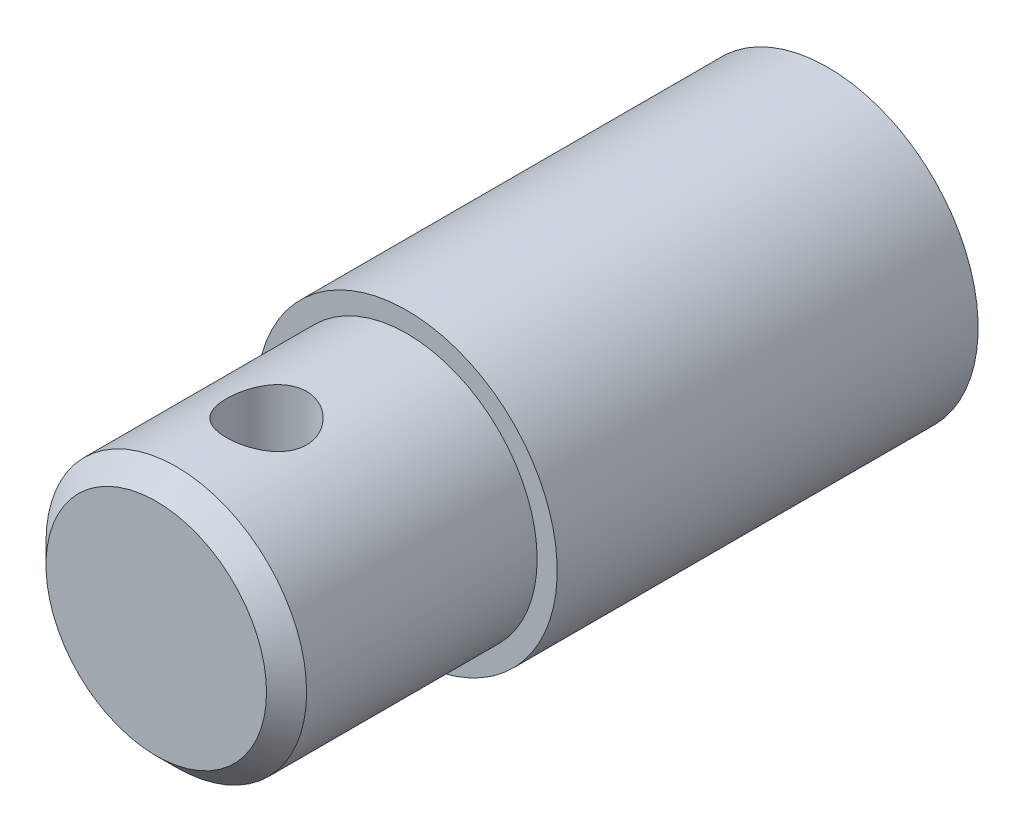
SolidWorks part; units mm, degrees
material "C40 or 38NiCrMo4"
ref_plane "Piano frontale" through (0, 0, 0) normal (0, 0, 1) x (1, 0, 0)
ref_plane "Piano superiore" through (0, 0, 0) normal (0, 1, 0) x (1, 0, 0)
ref_plane "Piano destro" through (0, 0, 0) normal (1, 0, 0) x (0, 0, -1)
sketch "Schizzo1" plane through (0, 0, 0) normal (0, 0, 1) x (1, 0, 0)
  circle A0 centre (0, 0) radius 15
  dimension "D1" = 30
extrude "Estrusione1" add sketch "Schizzo1" along normal blind 42
sketch "Schizzo2" plane through (0, 0, 42) normal (0, 0, 1) x (1, 0, 0)
  circle A0 centre (0, 0) radius 13
  dimension "D1" = 26
extrude "Estrusione2" add sketch "Schizzo2" along normal blind 25
chamfer "Smusso1" distance 2 angle 45 1 edges at (13, 0, 67)
sketch "Schizzo3" plane through (0, 0, 0) normal (0, 1, 0) x (1, 0, 0)
  line L0 (-13, -42) -> (13, -42) construction
  circle A0 centre (0, -56) radius 4
  dimension "D1" = 8
  dimension "D2" = 14
extrude "Estrusione3" cut sketch "Schizzo3" against normal through all and the other way through all
